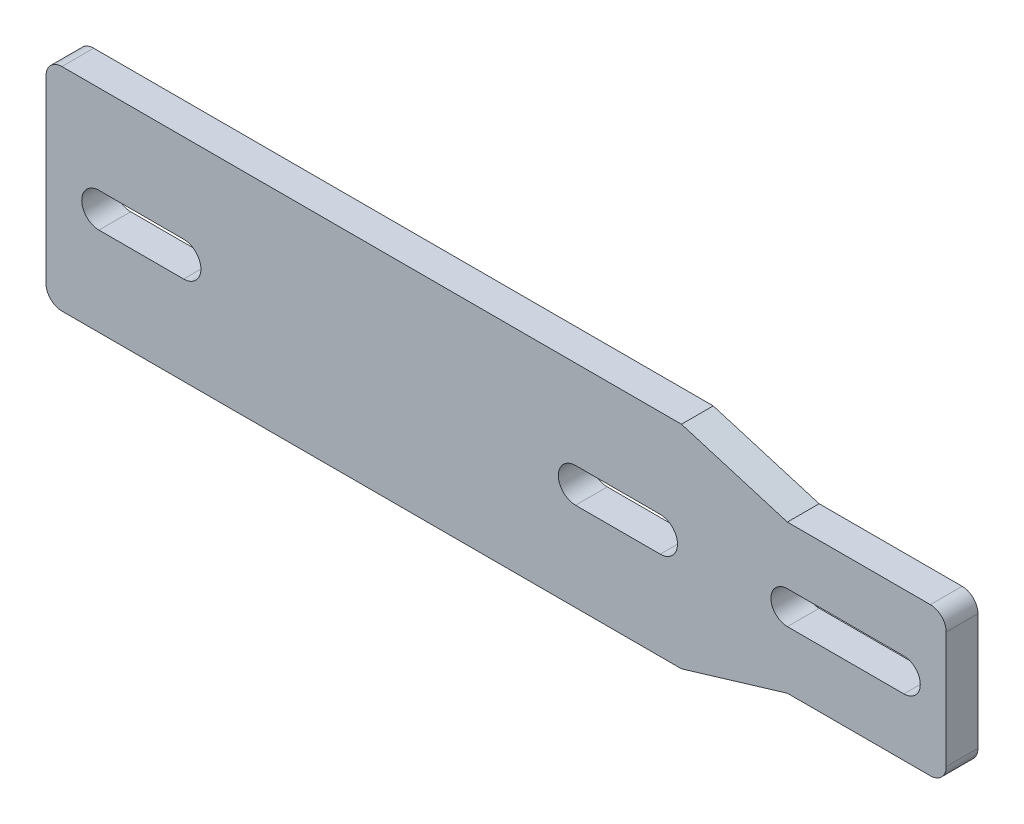
SolidWorks part; units mm, degrees
material "普通碳钢"
ref_plane "前视基准面" through (0, 0, 0) normal (0, 0, 1) x (1, 0, 0)
ref_plane "上视基准面" through (0, 0, 0) normal (0, 1, 0) x (1, 0, 0)
ref_plane "右视基准面" through (0, 0, 0) normal (1, 0, 0) x (0, 0, -1)
sketch "草图1" plane through (0, 0, 0) normal (0, 0, 1) x (1, 0, 0)
  line L0 (120, 40) -> (140, 34)
  line L1 (0, 0) -> (120, 0)
  line L2 (0, 0) -> (0, 40)
  line L3 (0, 40) -> (120, 40)
  line L5 (140, 34) -> (170, 34)
  line L6 (170, 34) -> (170, 6)
  line L7 (170, 6) -> (140, 6)
  line L8 (140, 6) -> (120, 0)
  line L10 (0, 20) -> (251.8547, 20) construction
  dimension "D1" = 40
  dimension "D2" = 170
  dimension "D3" = 30
  dimension "D4" = 28
  dimension "D5" = 120
extrude "凸台-拉伸1" add sketch "草图1" along normal blind 6
sketch "草图2" plane through (0, 0, 6) normal (0, 0, 1) x (1, 0, 0)
  line L0 (0, 20) -> (160.5732, 20) construction
  line L1 (0, 40) -> (0, 0) construction
  line L2 (10, 20) -> (26, 20) construction
  line L3 (10, 23.25) -> (26, 23.25)
  line L4 (10, 16.75) -> (26, 16.75)
  arc A0 (10, 23.25) -> (10, 16.75) centre (10, 20) ccw
  arc A1 (26, 16.75) -> (26, 23.25) centre (26, 20) ccw
  point P2 (18, 20)
  dimension "D1" = 3.25
  dimension "D2" = 16
  dimension "D3" = 10
extrude "切除-拉伸1" cut sketch "草图2" against normal blind 6
ref_plane "基准面1" through (0, 20, 0) normal (0, -1, 0) x (-1, 0, 0)
sketch "草图3" plane through (0, 0, 6) normal (0, 0, 1) x (1, 0, 0)
  line L0 (140, 20) -> (162, 20) construction
  line L1 (-3.3, 20) -> (3.3, 20) construction
  line L2 (140, 23.1) -> (162, 23.1)
  line L3 (140, 16.9) -> (162, 16.9)
  line L5 (170, 6) -> (170, 34) construction
  arc A0 (140, 23.1) -> (140, 16.9) centre (140, 20) ccw
  arc A1 (162, 16.9) -> (162, 23.1) centre (162, 20) ccw
  point P4 (151, 20)
  dimension "D1" = 3.1
  dimension "D3" = 8
  dimension "D2" = 22
extrude "切除-拉伸2" cut sketch "草图3" against normal blind 6
pattern_linear "阵列(线性)1" count 2 spacing 90 along (1, 0, 0) of "切除-拉伸1"
fillet "圆角1" radius 3 4 edges at (170, 6, 3) (170, 34, 3) (0, 40, 3) (0, 0, 3)
